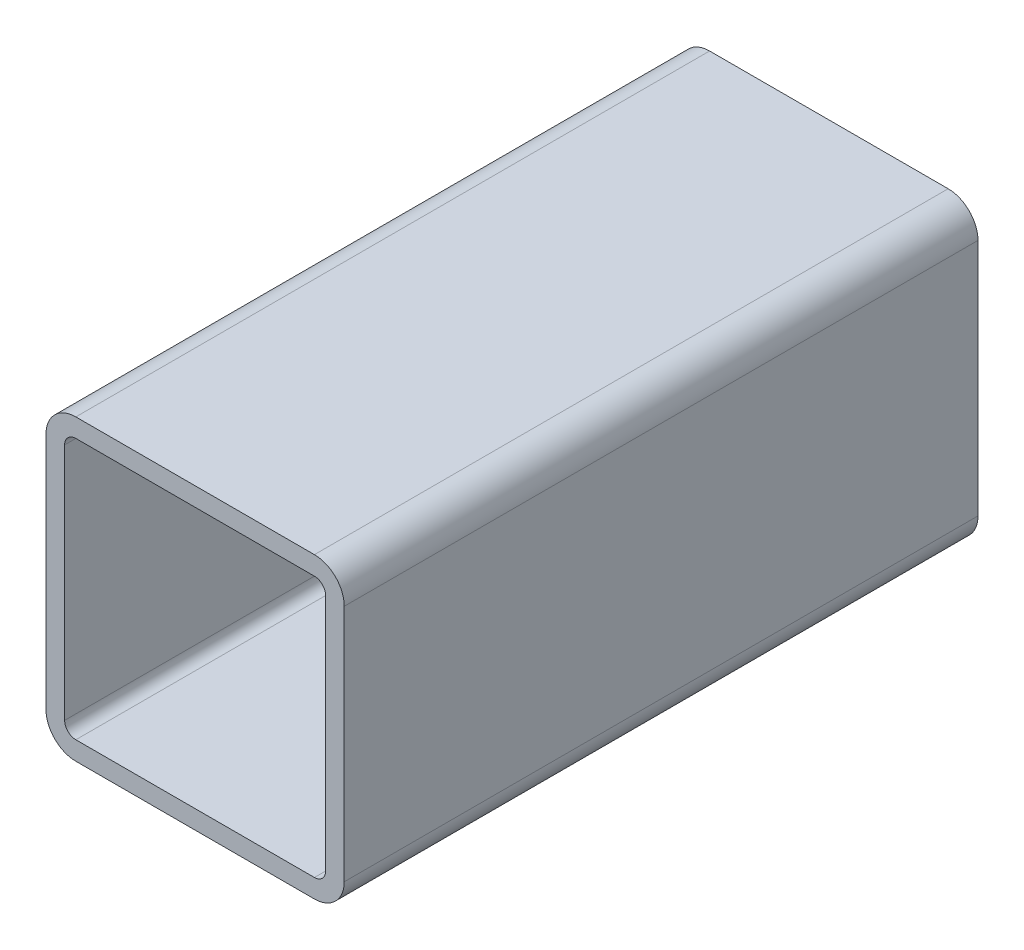
SolidWorks part; units mm, degrees
material "1.0037 (S235JR)"
ref_plane "Płaszczyzna przednia" through (0, 0, 0) normal (0, 0, 1) x (1, 0, 0)
ref_plane "Płaszczyzna górna" through (0, 0, 0) normal (0, 1, 0) x (1, 0, 0)
ref_plane "Płaszczyzna prawa" through (0, 0, 0) normal (1, 0, 0) x (0, 0, -1)
sketch "Szkic1" plane through (0, 0, 0) normal (0, 0, 1) x (1, 0, 0)
  line L0 (0, 8) -> (0, 72) construction
  line L1 (-8, 0) -> (-72, 0)
  line L2 (0, 8) -> (0, 72)
  line L3 (-8, 80) -> (-72, 80)
  line L4 (-80, 8) -> (-80, 72)
  line L5 (-560, 0) -> (0, 0) construction
  line L6 (-5, 8) -> (-5, 72)
  line L7 (-8, 75) -> (-72, 75)
  line L8 (-75, 8) -> (-75, 72)
  line L9 (-8, 5) -> (-72, 5)
  arc A0 (-8, 0) -> (0, 8) centre (-8, 8) ccw
  arc A1 (-80, 8) -> (-72, 0) centre (-72, 8) ccw
  arc A2 (-72, 80) -> (-80, 72) centre (-72, 72) ccw
  arc A3 (0, 72) -> (-8, 80) centre (-8, 72) ccw
  arc A4 (-8, 5) -> (-5, 8) centre (-8, 8) ccw
  arc A5 (-5, 72) -> (-8, 75) centre (-8, 72) ccw
  arc A6 (-72, 75) -> (-75, 72) centre (-72, 72) ccw
  arc A7 (-75, 8) -> (-72, 5) centre (-72, 8) ccw
  dimension "D1" = 8
  dimension "D2" = 8
  dimension "D3" = 8
  dimension "D4" = 8
  dimension "D5" = 80
  dimension "D6" = 80
  dimension "D7" = 5
extrude "Dodanie-wyciągnięcie1" add sketch "Szkic1" along normal up to surface (170 mm away)
